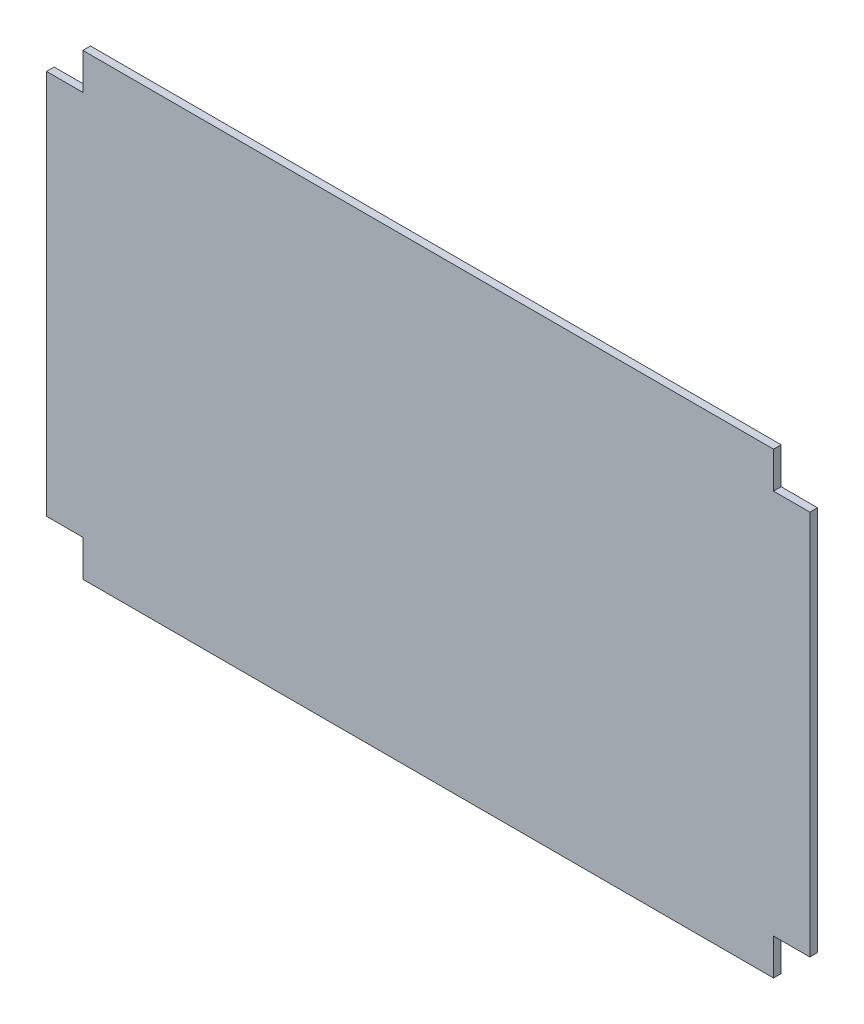
SolidWorks part; units mm, degrees
ref_plane "Front Plane" through (0, 0, 0) normal (0, 0, 1) x (1, 0, 0)
ref_plane "Top Plane" through (0, 0, 0) normal (0, 1, 0) x (1, 0, 0)
ref_plane "Right Plane" through (0, 0, 0) normal (1, 0, 0) x (0, 0, -1)
sketch "Sketch1" plane through (0, 0, 0) normal (0, 0, 1) x (1, 0, 0)
  line L1 (-635, 381) -> (635, 381)
  line L2 (-635, 381) -> (-635, -381)
  line L3 (-635, -381) -> (635, -381)
  line L4 (635, 381) -> (635, -381)
  line L5 (-635, 381) -> (635, -381) construction
  line L6 (-635, -381) -> (635, 381) construction
  point P0 (0, 0)
  dimension "D1" = 1270
  dimension "D2" = 762
extrude "Boss-Extrude1" add sketch "Sketch1" along normal blind 12.7
sketch "Sketch2" plane through (0, 0, 12.7) normal (0, 0, 1) x (1, 0, 0)
  line L0 (-635, 381) -> (-635, -381) construction
  line L1 (-635, 320.5) -> (-574.5, 320.5)
  line L2 (-635, 320.5) -> (-635, 381)
  line L3 (-635, 381) -> (-574.5, 381)
  line L4 (-574.5, 320.5) -> (-574.5, 381)
  line L5 (635, 381) -> (-635, 381) construction
  line L6 (574.5, 381) -> (635, 381)
  line L7 (574.5, 381) -> (574.5, 320.5)
  line L8 (574.5, 320.5) -> (635, 320.5)
  line L9 (635, 381) -> (635, 320.5)
  line L10 (635, -381) -> (635, 381) construction
  line L11 (-635, -381) -> (635, -381) construction
  line L12 (574.5, -381) -> (635, -381)
  line L13 (574.5, -381) -> (574.5, -320.5)
  line L14 (574.5, -320.5) -> (635, -320.5)
  line L15 (635, -381) -> (635, -320.5)
  line L17 (-635, -320.5) -> (-574.5, -320.5)
  line L18 (-635, -320.5) -> (-635, -381)
  line L19 (-635, -381) -> (-574.5, -381)
  line L20 (-574.5, -320.5) -> (-574.5, -381)
  dimension "D1" = 60.5
extrude "Cut-Extrude1" cut sketch "Sketch2" against normal through all
